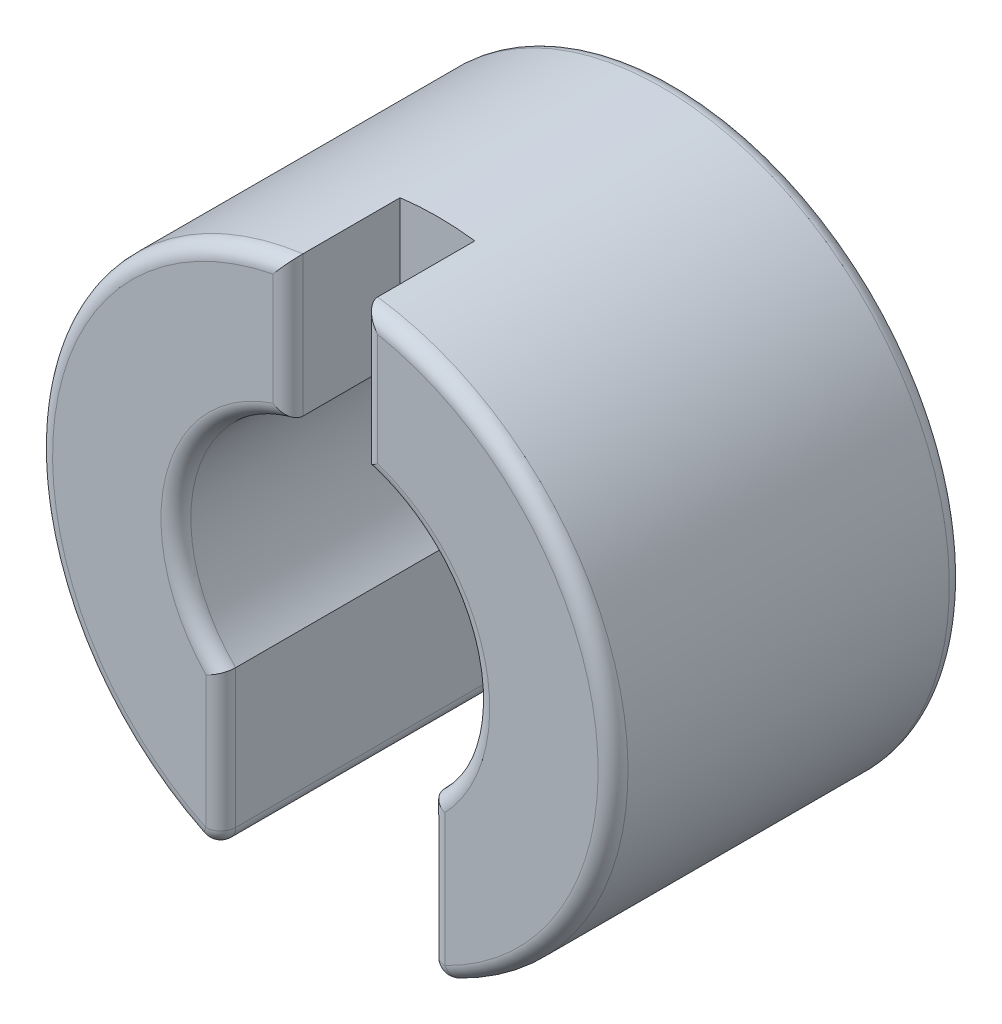
SolidWorks part; units mm, degrees
ref_plane "前视基准面" through (0, 0, 0) normal (0, 0, 1) x (1, 0, 0)
ref_plane "上视基准面" through (0, 0, 0) normal (0, 1, 0) x (1, 0, 0)
ref_plane "右视基准面" through (0, 0, 0) normal (1, 0, 0) x (0, 0, -1)
sketch "草图1" plane through (0, 0, 0) normal (0, 0, 1) x (1, 0, 0)
  line L2 (-1.4, -3.5864) -> (-1.4, -1.4283)
  line L4 (1.4, -3.5864) -> (1.4, -1.4283)
  arc A0 (1.4, -3.5864) -> (-1.4, -3.5864) centre (0, 0) ccw
  arc A1 (1.4, -1.4283) -> (-1.4, -1.4283) centre (0, 0) ccw
extrude "凸台-拉伸1" add sketch "草图1" along normal blind 4.7
sketch "草图2" plane through (0, 0, 4.7) normal (0, 0, 1) x (1, 0, 0)
  line L2 (-0.5, 1.9365) -> (-0.5, 3.8174)
  line L4 (0.5, 1.9365) -> (0.5, 3.8174)
  arc A0 (0.5, 1.9365) -> (-0.5, 1.9365) centre (0, 0) ccw
  arc A1 (0.5, 3.8174) -> (-0.5, 3.8174) centre (0, 0) ccw
extrude "切除-拉伸1" cut sketch "草图2" against normal blind 1.5
sketch "草图3" plane through (0, 0, 0) normal (0, 0, -1) x (-1, 0, 0)
  line L0 (-1.7678, -1.7678) -> (-2.4749, -2.4749)
  line L1 (1.7678, -1.7678) -> (2.4749, -2.4749)
  arc A0 (1.7678, -1.7678) -> (-1.7678, -1.7678) centre (0, 0) ccw
  arc A1 (2.4749, -2.4749) -> (-2.4749, -2.4749) centre (0, 0) ccw
extrude "切除-拉伸2" cut sketch "草图3" against normal blind 1.5
sketch "草图4" plane through (0, 0, 0) normal (0, 0, -1) x (-1, 0, 0)
  line L2 (-0.5, 1.9365) -> (-0.5, 2.245)
  line L4 (0.5, 1.9365) -> (0.5, 2.245)
  arc A0 (0.5, 1.9365) -> (-0.5, 1.9365) centre (0, 0) ccw
  arc A1 (0.5, 2.245) -> (-0.5, 2.245) centre (0, 0) ccw
extrude "切除-拉伸3" cut sketch "草图4" against normal through all
fillet "圆角1" radius 0.2 11 edges at (-1.9321, 0.5168, 4.7) (-1.4, -2.5074, 4.7) (-3.8219, 0.4646, 4.7) (-0.5, 2.8769, 4.7) (3.8219, 0.4646, 4.7) (1.4, -2.5074, 4.7) (1.9321, 0.5168, 4.7) (0.5, 2.8769, 4.7) (0, 3.85, 0) (1.4, -3.5864, 2.35) (-1.4, -3.5864, 2.35)
